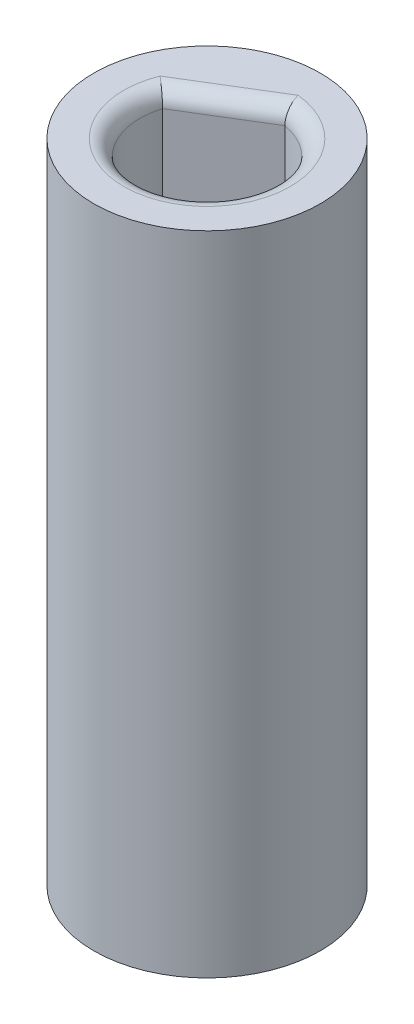
SolidWorks part; units mm, degrees
ref_plane "Front Plane" through (0, 0, 0) normal (0, 0, 1) x (1, 0, 0)
ref_plane "Top Plane" through (0, 0, 0) normal (0, 1, 0) x (1, 0, 0)
ref_plane "Right Plane" through (0, 0, 0) normal (1, 0, 0) x (0, 0, -1)
sketch "Sketch1" plane through (0, 0, 0) normal (0, 1, 0) x (1, 0, 0)
  line L0 (-3.9671, 1.2185) -> (0.7262, 4.086)
  circle A0 centre (0, 0) radius 4.15
  circle A1 centre (0, 0) radius 7
extrude "Boss-Extrude1" add sketch "Sketch1" along normal blind 40 contours A1 A0 | L0 A0
fillet "Fillet1" radius 1 2 edges at (-1.6204, 40, -2.6522) (2.1637, 40, 3.5413)
sketch "Sketch2" plane through (0, 0, 0) normal (0, -1, 0) x (1, 0, 0)
  circle A0 centre (0, 0) radius 4.15
extrude "Boss-Extrude2" add sketch "Sketch2" against normal blind 10
